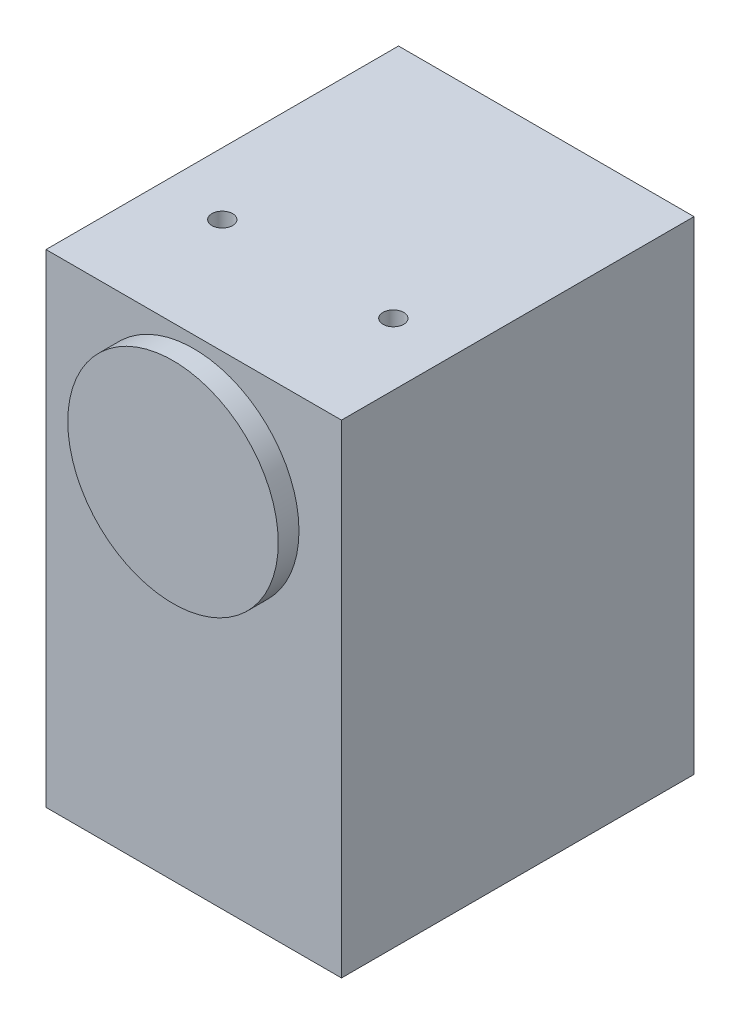
SolidWorks part; units mm, degrees
material "PUR"
ref_plane "Plan de face" through (0, 0, 0) normal (0, 0, 1) x (1, 0, 0)
ref_plane "Plan de dessus" through (0, 0, 0) normal (0, 1, 0) x (1, 0, 0)
ref_plane "Plan de droite" through (0, 0, 0) normal (1, 0, 0) x (0, 0, -1)
sketch "Esquisse1" plane through (0, 0, 0) normal (0, 0, 1) x (1, 0, 0)
  line L1 (-14.25, -23.3) -> (14.25, -23.3)
  line L2 (-14.25, -23.3) -> (-14.25, 23.3)
  line L3 (-14.25, 23.3) -> (14.25, 23.3)
  line L4 (14.25, -23.3) -> (14.25, 23.3)
  line L5 (-14.25, -23.3) -> (14.25, 23.3) construction
  line L6 (-14.25, 23.3) -> (14.25, -23.3) construction
  point P0 (0, 0)
  dimension "D1" = 28.5
  dimension "D2" = 46.6
extrude "Boss.-Extru.1" add sketch "Esquisse1" along normal blind 34
sketch "Esquisse2" plane through (0, 0, 34) normal (0, 0, 1) x (1, 0, 0)
  line L0 (14.25, 23.3) -> (-14.25, 23.3) construction
  circle A0 centre (0, 12) radius 10.15
  dimension "D1" = 20.3
  dimension "D2" = 11.3
extrude "Boss.-Extru.2" add sketch "Esquisse2" along normal blind 2
sketch "Esquisse3" plane through (0, 23.3, 0) normal (0, 1, 0) x (1, 0, 0)
  line L1 (14.25, -34) -> (-14.25, -34) construction
  line L3 (14.25, -34) -> (14.25, 0) construction
  circle A0 centre (-8.25, -23) radius 1
  circle A1 centre (8.25, -23) radius 1
  dimension "D1" = 2
  dimension "D2" = 16.5
  dimension "D3" = 6
  dimension "D4" = 11
extrude "Enlèv. mat.-Extru.1" cut sketch "Esquisse3" against normal blind 2
